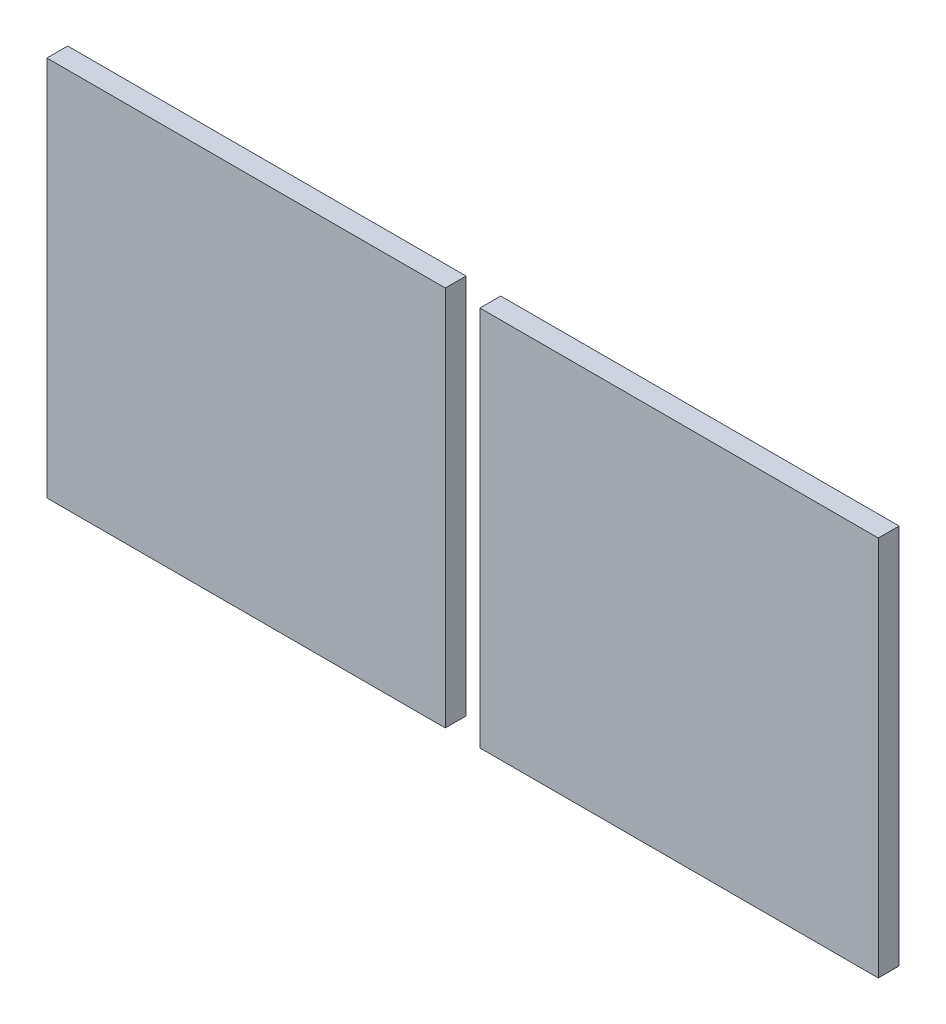
SolidWorks part; units mm, degrees
material "Acrylic (Medium-high impact)"
ref_plane "Front Plane" through (0, 0, 0) normal (0, 0, 1) x (1, 0, 0)
ref_plane "Top Plane" through (0, 0, 0) normal (0, 1, 0) x (1, 0, 0)
ref_plane "Right Plane" through (0, 0, 0) normal (1, 0, 0) x (0, 0, -1)
sketch "Sketch1" plane through (0, 0, 0) normal (0, 0, 1) x (1, 0, 0)
  line L1 (0, 0) -> (120, 0) construction
  line L2 (0, 0) -> (0, 55) construction
  line L3 (0, 55) -> (120, 55) construction
  line L4 (120, 0) -> (120, 55) construction
  line L5 (0, 0) -> (57.5, 0)
  line L6 (0, 0) -> (0, 55)
  line L7 (0, 55) -> (57.5, 55)
  line L8 (57.5, 0) -> (57.5, 55)
  line L9 (120, 55) -> (62.5, 55)
  line L10 (120, 55) -> (120, 0)
  line L11 (120, 0) -> (62.5, 0)
  line L12 (62.5, 55) -> (62.5, 0)
  dimension "D1" = 120
  dimension "D2" = 55
  dimension "D3" = 5
  dimension "D4" = 57.5
extrude "Boss-Extrude1" add sketch "Sketch1" against normal blind 3
